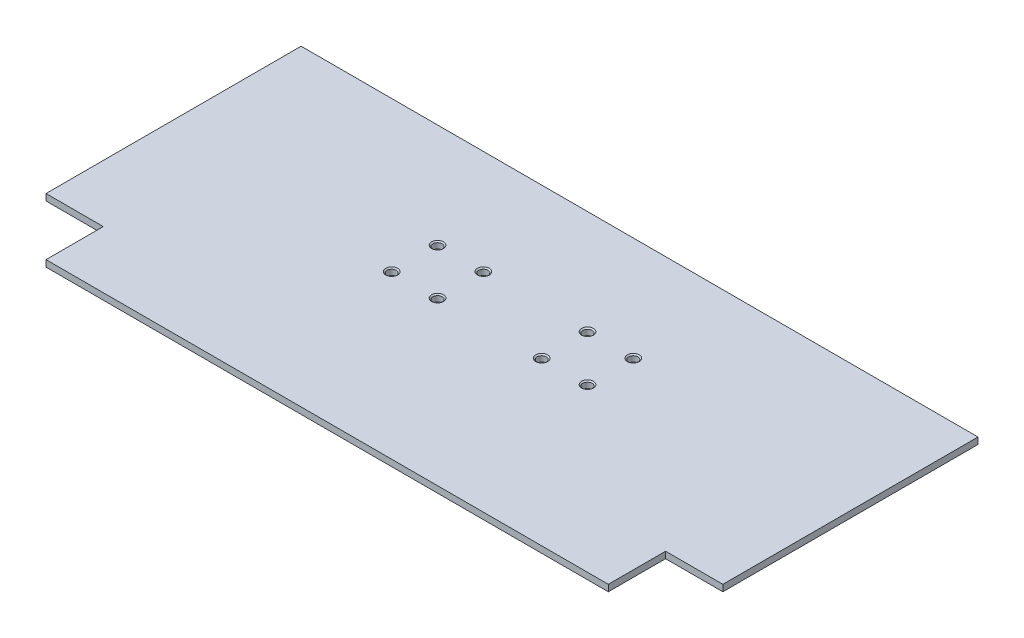
SolidWorks part; units mm, degrees
ref_plane "Front Plane" through (0, 0, 0) normal (0, 0, 1) x (1, 0, 0)
ref_plane "Top Plane" through (0, 0, 0) normal (0, 1, 0) x (1, 0, 0)
ref_plane "Right Plane" through (0, 0, 0) normal (1, 0, 0) x (0, 0, -1)
sketch "Sketch1" plane through (0, 0, 0) normal (0, 1, 0) x (1, 0, 0)
  line L1 (-165.1, 101.6) -> (165.1, 101.6)
  line L2 (-165.1, 101.6) -> (-165.1, -22.86)
  line L3 (-137.16, -50.8) -> (137.16, -50.8)
  line L4 (165.1, 101.6) -> (165.1, -22.86)
  line L5 (-165.1, 101.6) -> (165.1, -101.6) construction
  line L6 (-165.1, -101.6) -> (165.1, 101.6) construction
  line L13 (-165.1, -22.86) -> (-137.16, -22.86)
  line L14 (-137.16, -50.8) -> (-137.16, -22.86)
  line L20 (165.1, -101.6) -> (165.1, -22.86)
  line L21 (165.1, -22.86) -> (137.16, -22.86)
  line L22 (137.16, -50.8) -> (137.16, -22.86)
  point P0 (0, 0)
  dimension "D1" = 152.4
  dimension "D2" = 330.2
  dimension "D3" = 27.94
  dimension "D4" = 27.94
  dimension "D5" = 27.94
  dimension "D6" = 27.94
extrude "Boss-Extrude1" add sketch "Sketch1" along normal blind 3.175 contours L3 L22 L21 L4 L1 L2 L13 L14
sketch "Sketch2" plane through (0, 3.175, 0) normal (0, 1, 0) x (1, 0, 0)
  line L0 (0, 171.0042) -> (0, -126.1727) construction
  line L1 (-165.1, 101.6) -> (165.1, 101.6) construction
  point P0 (-47.752, 28.448)
  point P5 (-25.4, 28.448)
  point P6 (-25.4, 50.8)
  point P7 (-47.752, 50.8)
  point P8 (47.752, 50.8)
  point P9 (25.4, 50.8)
  point P11 (25.4, 28.448)
  point P12 (47.752, 28.448)
  dimension "D3" = 25.4
  dimension "D4" = 50.8
  dimension "D1" = 2
  dimension "D2" = 2
hole_wizard "#16 (0.177) Diameter Hole1" positions "Sketch4" profile "Sketch6" hole size "#16" standard "ANSI Inch"
sketch "Sketch4" plane through (0, 3.175, 0) normal (0, 1, 0) x (1, 0, 0)
  point P0 (-47.752, 50.8)
  point P3 (-25.4, 50.8)
  point P6 (-25.4, 28.448)
  point P9 (-47.752, 28.448)
  point P12 (25.4, 28.448)
  point P15 (25.4, 50.8)
  point P18 (47.752, 50.8)
  point P21 (47.752, 28.448)
sketch "Sketch6" plane through (-47.752, 3.175, -50.8) normal (1, 0, 0) x (0, 0, 1)
  line L0 (0, 0) -> (0, 4.5257)
  line L1 (0, 4.5257) -> (2.2479, 3.175)
  line L2 (2.2479, 3.175) -> (2.2479, 0.5328)
  line L3 (2.2479, 0.5328) -> (2.8829, 0)
  line L5 (2.8829, 0) -> (0, 0)
  line L6 (-2.2479, 0.5328) -> (-2.8829, 0) construction
  line L10 (0, 4.5257) -> (-2.2479, 3.175) construction
  line L11 (0, -6.35) -> (0, 107.95) construction
  dimension "Hole Dia." = 4.4958
  dimension "Hole Depth" = 3.175
  dimension "Near C'Sink Dia." = 5.7658
  dimension "Near C'Sink Angle" = 100
  dimension "Drill Angle" = 118
